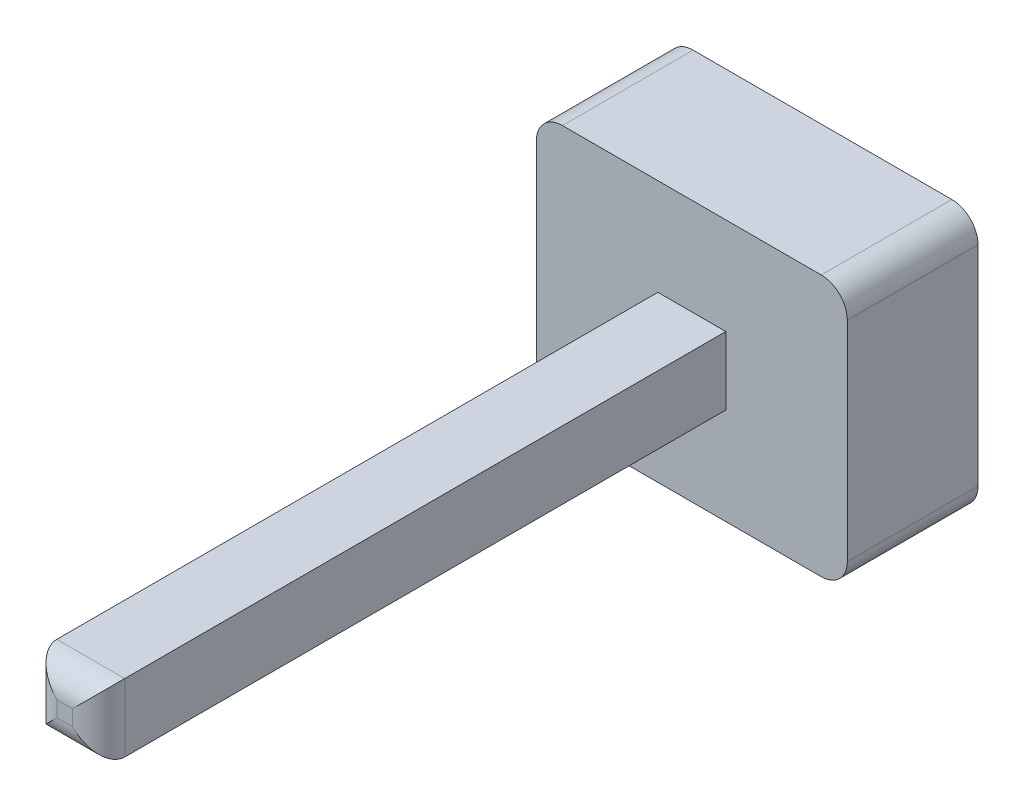
SolidWorks part; units mm, degrees
ref_plane "Front Plane" through (0, 0, 0) normal (0, 0, 1) x (1, 0, 0)
ref_plane "Top Plane" through (0, 0, 0) normal (0, 1, 0) x (1, 0, 0)
ref_plane "Right Plane" through (0, 0, 0) normal (1, 0, 0) x (0, 0, -1)
ref_plane "Plane1" through (0, 0, 1.27) normal (0, 0, 1) x (1, 0, 0)
sketch "Sketch1" plane through (0, 0, 1.27) normal (0, 0, 1) x (1, 0, 0)
  line L0 (-0.6632, 1.6921) -> (-0.6632, 3.7241)
  line L1 (-0.9172, 3.9781) -> (-3.4318, 3.9781)
  line L2 (-3.6858, 3.7241) -> (-3.6858, 1.6921)
  line L3 (-3.4318, 1.4381) -> (-0.9172, 1.4381)
  arc A0 (-0.9172, 1.4381) -> (-0.6632, 1.6921) centre (-0.9172, 1.6921) ccw
  arc A1 (-0.6632, 3.7241) -> (-0.9172, 3.9781) centre (-0.9172, 3.7241) ccw
  arc A2 (-3.4318, 3.9781) -> (-3.6858, 3.7241) centre (-3.4318, 3.7241) ccw
  arc A3 (-3.6858, 1.6921) -> (-3.4318, 1.4381) centre (-3.4318, 1.6921) ccw
extrude "Boss-Extrude1" add sketch "Sketch1" against normal blind 1.27
ref_plane "Plane2" through (0, 0, 7.366) normal (0, 0, 1) x (1, 0, 0)
sketch "Sketch2" plane through (0, 0, 7.366) normal (0, 0, 1) x (1, 0, 0)
  line L0 (-1.8443, 3.0383) -> (-2.5047, 3.0383)
  line L1 (-2.5047, 3.0383) -> (-2.5047, 2.3779)
  line L2 (-2.5047, 2.3779) -> (-1.8443, 2.3779)
  line L3 (-1.8443, 2.3779) -> (-1.8443, 3.0383)
extrude "Boss-Extrude2" add sketch "Sketch2" against normal up to surface (6.096 mm away) up to face at (-2.1745, 2.7081, 1.27)
fillet "Fillet1" radius 0.254 4 edges at (-2.1745, 2.3779, 7.366) (-1.8443, 2.7081, 7.366) (-2.5047, 2.7081, 7.366) (-2.1745, 3.0383, 7.366)
